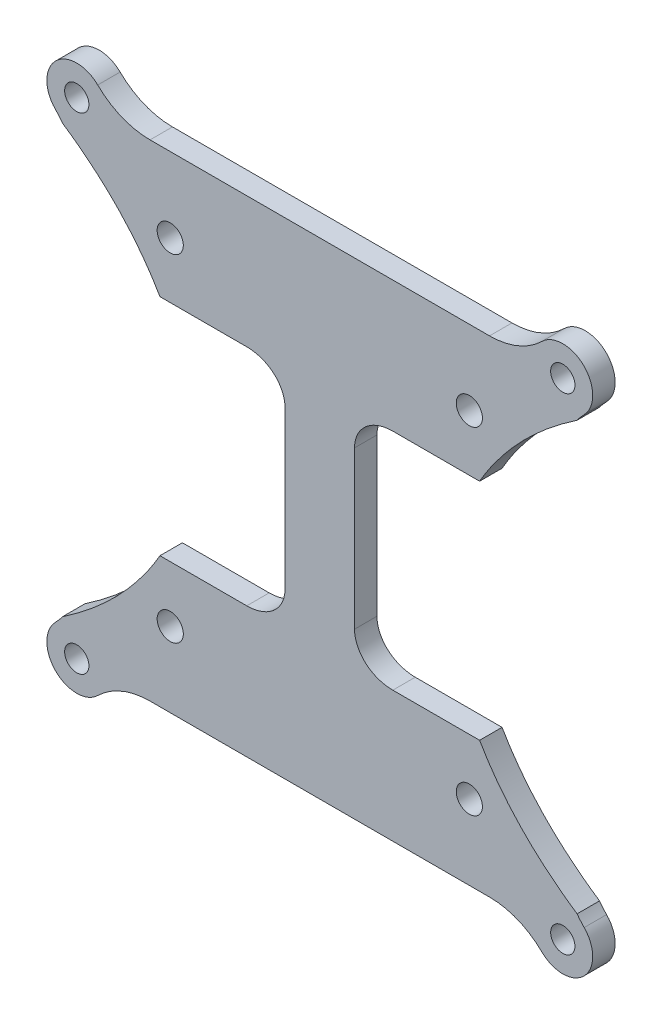
SolidWorks part; units mm, degrees
material "ABS"
ref_plane "Спереди" through (0, 0, 0) normal (0, 0, 1) x (1, 0, 0)
ref_plane "Сверху" through (0, 0, 0) normal (0, 1, 0) x (1, 0, 0)
ref_plane "Справа" through (0, 0, 0) normal (1, 0, 0) x (0, 0, -1)
sketch "Эскиз1" plane through (0, 0, 0) normal (0, 0, 1) x (1, 0, 0)
  line L1 (-32.5, -32.5) -> (32.5, -32.5)
  line L2 (-32.5, -32.5) -> (-32.5, 32.5)
  line L3 (-32.5, 32.5) -> (32.5, 32.5)
  line L4 (32.5, -32.5) -> (32.5, 32.5)
  line L5 (-32.5, -32.5) -> (32.5, 32.5) construction
  line L6 (-32.5, 32.5) -> (32.5, -32.5) construction
  circle A0 centre (-32.5, 32.5) radius 1.625
  arc A1 (-28.5, 32.5) -> (-32.5, 28.5) centre (-32.5, 32.5) ccw
  circle A2 centre (32.5, 32.5) radius 1.625
  arc A3 (32.5, 28.5) -> (28.5, 32.5) centre (32.5, 32.5) ccw
  circle A4 centre (32.5, -32.5) radius 1.625
  arc A5 (28.5, -32.5) -> (32.5, -28.5) centre (32.5, -32.5) ccw
  circle A6 centre (-32.5, -32.5) radius 1.625
  arc A7 (-32.5, -28.5) -> (-28.5, -32.5) centre (-32.5, -32.5) ccw
  point P0 (0, 0)
  point P20 (0, 0)
  dimension "D2" = 3.25
  dimension "D3" = 8
  dimension "D1" = 65
  dimension "D4" = 4
extrude "Бобышка-Вытянуть1" add sketch "Эскиз1" along normal blind 3 contours A6 L1 A4 L4 A2 L3 A0 L2 | L3 A1 L2 A0 | L4 A3 L3 A2 | L1 A5 L4 A4 | L2 A7 L1 A6
fillet "Скругление1" radius 10 8 edges at (-28.5, -32.5, 1.5) (-32.5, -28.5, 1.5) (-28.5, 32.5, 1.5) (-32.5, 28.5, 1.5) (28.5, 32.5, 1.5) (32.5, 28.5, 1.5) (32.5, -28.5, 1.5) (28.5, -32.5, 1.5)
sketch "Эскиз2" plane through (0, 0, 3) normal (0, 0, 1) x (1, 0, 0)
  line L0 (0, 32.5) -> (0, -32.5) construction
  line L1 (-22.702, 32.5) -> (22.702, 32.5) construction
  line L2 (-22.702, -32.5) -> (22.702, -32.5) construction
  line L3 (-32.5, 0) -> (32.5, 0) construction
  line L4 (-32.5, -22.702) -> (-32.5, 22.702) construction
  line L5 (32.5, -22.702) -> (32.5, 22.702) construction
  line L6 (-32.5, 22.5) -> (32.5, 22.5) construction
  circle A0 centre (-20, 22.5) radius 1.75
  circle A1 centre (20, 22.5) radius 1.75
  circle A2 centre (20, -22.5) radius 1.75
  circle A3 centre (-20, -22.5) radius 1.75
  dimension "D2" = 3.5
  dimension "D1" = 10
  dimension "D3" = 20
extrude "Вырез-Вытянуть1" cut sketch "Эскиз2" against normal blind 10
sketch "Эскиз3" plane through (0, 0, 3) normal (0, 0, 1) x (1, 0, 0)
  line L4 (-38.7591, -11.8255) -> (-40.1734, -10.8255)
  line L5 (-38.7591, -18.1012) -> (-38.7591, -11.8255)
  line L6 (-40.1734, -19.1012) -> (-38.7591, -18.1012)
  line L7 (-40.1734, -10.8255) -> (-40.1734, -19.1012)
  line L8 (-38.7591, -11.8255) -> (-40.1734, -10.8255)
  line L9 (-38.7591, -18.1012) -> (-38.7591, -11.8255)
  line L10 (-40.1734, -19.1012) -> (-38.7591, -18.1012)
  line L11 (-40.1734, -10.8255) -> (-40.1734, -19.1012)
  line L12 (38.7591, 11.8255) -> (40.1734, 10.8255)
  line L13 (38.7591, 18.1012) -> (38.7591, 11.8255)
  line L14 (-82.0001, -12.7701) -> (-81.8151, -12.8801)
  line L15 (-80.9227, -13.8292) -> (-80.0272, -15.612)
  line L16 (-79.1335, -15.9875) -> (-75.9847, -15.2389)
  line L17 (-75.694, 15.2742) -> (-79.1811, 15.9349)
  line L18 (-80.0623, 15.5421) -> (-80.9227, 13.8292)
  line L19 (-81.7613, 12.9159) -> (-81.993, 12.7739)
  line L20 (-82.0001, -12.7701) -> (-81.8151, -12.8801)
  line L21 (-80.9227, -13.8292) -> (-80.0272, -15.612)
  line L22 (-79.1335, -15.9875) -> (-75.9847, -15.2389)
  line L23 (-75.694, 15.2742) -> (-79.1811, 15.9349)
  line L24 (-80.0623, 15.5421) -> (-80.9227, 13.8292)
  line L25 (-81.7613, 12.9159) -> (-81.993, 12.7739)
  line L26 (40.1734, 19.1012) -> (38.7591, 18.1012)
  line L27 (40.1734, 10.8255) -> (40.1734, 19.1012)
  line L28 (38.7591, 11.8255) -> (40.1734, 10.8255)
  line L29 (38.7591, 18.1012) -> (38.7591, 11.8255)
  line L30 (40.1734, 19.1012) -> (38.7591, 18.1012)
  line L31 (40.1734, 10.8255) -> (40.1734, 19.1012)
  line L34 (-23.5994, 5.6485) -> (-23.5994, -5.6485)
  line L35 (-68.4576, -33.9999) -> (-68.4575, -34.4102)
  line L36 (-23.1698, -12) -> (-9.7678, -12)
  line L37 (-7.6464, -10.5) -> (-7.6464, 10.5)
  line L38 (-9.7678, 12) -> (-23.1698, 12)
  line L39 (-68.4576, 34.4102) -> (-68.4576, 33.9999)
  line L40 (-23.5994, 5.6485) -> (-23.5994, -5.6485)
  line L41 (-68.4576, -33.9999) -> (-68.4575, -34.4102)
  line L42 (-23.1698, -12) -> (-9.7678, -12)
  line L43 (-7.6464, -10.5) -> (-7.6464, 10.5)
  line L44 (-9.7678, 12) -> (-23.1698, 12)
  line L45 (-68.4576, 34.4102) -> (-68.4576, 33.9999)
  line L46 (82.0001, 12.7701) -> (81.8151, 12.8801)
  line L47 (80.9227, 13.8292) -> (80.0272, 15.612)
  line L48 (79.1335, 15.9875) -> (75.9847, 15.2389)
  line L49 (75.694, -15.2742) -> (79.1811, -15.9349)
  line L50 (80.0623, -15.5421) -> (80.9227, -13.8292)
  line L51 (81.7613, -12.9159) -> (81.993, -12.7739)
  line L52 (82.0001, 12.7701) -> (81.8151, 12.8801)
  line L53 (80.9227, 13.8292) -> (80.0272, 15.612)
  line L54 (79.1335, 15.9875) -> (75.9847, 15.2389)
  line L55 (75.694, -15.2742) -> (79.1811, -15.9349)
  line L56 (80.0623, -15.5421) -> (80.9227, -13.8292)
  line L57 (81.7613, -12.9159) -> (81.993, -12.7739)
  line L58 (23.5994, -5.6485) -> (23.5994, 5.6485)
  line L59 (68.4576, 33.9999) -> (68.4576, 34.4102)
  line L60 (23.1698, 12) -> (9.7678, 12)
  line L61 (7.6464, 10.5) -> (7.6464, -10.5)
  line L62 (9.7678, -12) -> (23.1698, -12)
  line L63 (68.4576, -34.4102) -> (68.4576, -33.9999)
  line L64 (23.5994, -5.6485) -> (23.5994, 5.6485)
  line L65 (68.4576, 33.9999) -> (68.4576, 34.4102)
  line L66 (23.1698, 12) -> (9.7678, 12)
  line L67 (7.6464, 10.5) -> (7.6464, -10.5)
  line L68 (9.7678, -12) -> (23.1698, -12)
  line L69 (68.4576, -34.4102) -> (68.4576, -33.9999)
  line L70 (71.4576, -34.4101) -> (71.4576, -31.1169)
  line L71 (9.7678, -15) -> (21.3752, -15)
  line L72 (4.6464, 10.5) -> (4.6464, -10.5)
  line L73 (21.3752, 15) -> (9.7678, 15)
  line L74 (71.4576, 31.1169) -> (71.4576, 34.4102)
  line L75 (26.5994, -5.2847) -> (26.5994, 5.2847)
  line L76 (71.4576, -34.4101) -> (71.4576, -31.1169)
  line L77 (9.7678, -15) -> (21.3752, -15)
  line L78 (4.6464, 10.5) -> (4.6464, -10.5)
  line L79 (21.3752, 15) -> (9.7678, 15)
  line L80 (71.4576, 31.1169) -> (71.4576, 34.4102)
  line L81 (26.5994, -5.2847) -> (26.5994, 5.2847)
  line L82 (-71.4576, 34.4109) -> (-71.4577, 31.1169)
  line L83 (-9.7678, 15) -> (-21.3752, 15)
  line L84 (-4.6464, -10.5) -> (-4.6464, 10.5)
  line L85 (-21.3752, -15) -> (-9.7678, -15)
  line L86 (-71.4587, -31.117) -> (-71.4575, -34.4505)
  line L87 (-26.5994, 5.2847) -> (-26.5994, -5.2847)
  line L88 (-71.4576, 34.4109) -> (-71.4577, 31.1169)
  line L89 (-9.7678, 15) -> (-21.3752, 15)
  line L90 (-4.6464, -10.5) -> (-4.6464, 10.5)
  line L91 (-21.3752, -15) -> (-9.7678, -15)
  line L92 (-71.4587, -31.117) -> (-71.4575, -34.4505)
  line L93 (-26.5994, 5.2847) -> (-26.5994, -5.2847)
  spline S1 degree 3 poles (-10.4749, -7.5) (-10.4749, -3.5) (-16.1317, -3.5) (-16.1317, -7.5) (-16.1317, -11.5) (-10.4749, -11.5) (-10.4749, -7.5) (-10.4749, -3.5) (-16.1317, -3.5) knots -0.5 0 0 0 0.5 0.5 0.5 1 1 1 1.5 1.5 1.5 weights 1 0.333333 0.333333 1 0.333333 0.333333 1 0.333333 0.333333 only from (-10.4749, -7.5) to (-10.4749, -7.5)
  spline S2 degree 3 poles (-10.4749, -7.5) (-10.4749, -3.5) (-16.1317, -3.5) (-16.1317, -7.5) (-16.1317, -11.5) (-10.4749, -11.5) (-10.4749, -7.5) (-10.4749, -3.5) (-16.1317, -3.5) knots -0.5 0 0 0 0.5 0.5 0.5 1 1 1 1.5 1.5 1.5 weights 1 0.333333 0.333333 1 0.333333 0.333333 1 0.333333 0.333333 only from (-10.4749, -7.5) to (-10.4749, -7.5)
  spline S3 degree 3 poles (-10.4749, 7.5) (-10.4749, 11.5) (-16.1317, 11.5) (-16.1317, 7.5) (-16.1317, 3.5) (-10.4749, 3.5) (-10.4749, 7.5) (-10.4749, 11.5) (-16.1317, 11.5) knots -0.5 0 0 0 0.5 0.5 0.5 1 1 1 1.5 1.5 1.5 weights 1 0.333333 0.333333 1 0.333333 0.333333 1 0.333333 0.333333 only from (-10.4749, 7.5) to (-10.4749, 7.5)
  spline S4 degree 3 poles (-10.4749, 7.5) (-10.4749, 11.5) (-16.1317, 11.5) (-16.1317, 7.5) (-16.1317, 3.5) (-10.4749, 3.5) (-10.4749, 7.5) (-10.4749, 11.5) (-16.1317, 11.5) knots -0.5 0 0 0 0.5 0.5 0.5 1 1 1 1.5 1.5 1.5 weights 1 0.333333 0.333333 1 0.333333 0.333333 1 0.333333 0.333333 only from (-10.4749, 7.5) to (-10.4749, 7.5)
  spline S5 degree 3 poles (10.4749, 7.5) (10.4749, 3.5) (16.1317, 3.5) (16.1317, 7.5) (16.1317, 11.5) (10.4749, 11.5) (10.4749, 7.5) (10.4749, 3.5) (16.1317, 3.5) knots -0.5 0 0 0 0.5 0.5 0.5 1 1 1 1.5 1.5 1.5 weights 1 0.333333 0.333333 1 0.333333 0.333333 1 0.333333 0.333333 only from (10.4749, 7.5) to (10.4749, 7.5)
  spline S6 degree 3 poles (10.4749, 7.5) (10.4749, 3.5) (16.1317, 3.5) (16.1317, 7.5) (16.1317, 11.5) (10.4749, 11.5) (10.4749, 7.5) (10.4749, 3.5) (16.1317, 3.5) knots -0.5 0 0 0 0.5 0.5 0.5 1 1 1 1.5 1.5 1.5 weights 1 0.333333 0.333333 1 0.333333 0.333333 1 0.333333 0.333333 only from (10.4749, 7.5) to (10.4749, 7.5)
  spline S7 degree 3 poles (10.4749, -7.5) (10.4749, -11.5) (16.1317, -11.5) (16.1317, -7.5) (16.1317, -3.5) (10.4749, -3.5) (10.4749, -7.5) (10.4749, -11.5) (16.1317, -11.5) knots -0.5 0 0 0 0.5 0.5 0.5 1 1 1 1.5 1.5 1.5 weights 1 0.333333 0.333333 1 0.333333 0.333333 1 0.333333 0.333333 only from (10.4749, -7.5) to (10.4749, -7.5)
  spline S8 degree 3 poles (10.4749, -7.5) (10.4749, -11.5) (16.1317, -11.5) (16.1317, -7.5) (16.1317, -3.5) (10.4749, -3.5) (10.4749, -7.5) (10.4749, -11.5) (16.1317, -11.5) knots -0.5 0 0 0 0.5 0.5 0.5 1 1 1 1.5 1.5 1.5 weights 1 0.333333 0.333333 1 0.333333 0.333333 1 0.333333 0.333333 only from (10.4749, -7.5) to (10.4749, -7.5)
  spline S16 degree 3 poles (-23.5994, -5.6485) (-27.4964, -22.0038) (-45.0004, -33.0667) (-68.4576, -33.9999) knots 0 0 0 0 1 1 1 1 weights 1 0.854251 0.854251 1
  spline S17 degree 3 poles (-2063.8023, -169.9528) (-48.9095, -26.3357) (-68.9345, -31.2035) (-68.4405, -34.6081) (-68.4142, -34.7204) (-68.3493, -34.9029) (-68.2007, -35.1493) (-67.9533, -35.395) (-67.6517, -35.5947) (-67.3374, -35.7342) (-66.9897, -35.8321) (-66.6982, -35.8734) (-60.2525, -36.1728) (-54.0031, -9.3917) (-42.6478, -2035.6643) knots -3.357469 -3.357469 -3.357469 -3.357469 0.033193 0.06659 0.100333 0.149309 0.261141 0.386702 0.497425 0.623884 0.731384 0.860481 0.9194 7.225792 7.225792 7.225792 7.225792 only from (-68.4575, -34.4102) to (-66.2132, -35.8754)
  spline S18 degree 3 poles (1480.429, 1254.4685) (-52.2846, 6.6497) (-74.2357, 20.3281) (-85.9765, 10.0439) (-86.2382, 9.8032) (-86.4915, 9.5581) (-86.9723, 9.0696) (-87.637, 8.3075) (-88.4098, 7.2278) (-89.1848, 5.8925) (-89.8783, 4.2706) (-90.3804, 2.3398) (-90.5866, 0.3596) (-90.489, -1.6318) (-90.0914, -3.5903) (-89.4067, -5.4592) (-88.4482, -7.2191) (-87.5257, -8.4479) (-86.7993, -9.2478) (-86.3671, -9.6837) (-66.7238, -27.9076) (32.2772, -15.1108) (-1144.9131, 1684.0441) knots -1.888033 -1.888033 -1.888033 -1.888033 0.014985 0.029837 0.044559 0.059151 0.073617 0.129706 0.184548 0.238313 0.321232 0.402799 0.485249 0.567587 0.649509 0.732567 0.813893 0.897623 0.92268 0.948089 0.973859 4.292326 4.292326 4.292326 4.292326 only from (-85.4284, 10.5101) to (-85.4283, -10.5101)
  spline S19 degree 3 poles (-85.4283, -10.5101) (-84.3984, -11.3461) (-83.2515, -12.1021) (-82.0001, -12.7701) knots 0 0 0 0 1 1 1 1 weights 1 0.996415 0.996415 1
  spline S20 degree 3 poles (-1326.947, 1552.1577) (-12.7734, -66.3768) (-85.4859, -10.1805) (-81.5604, -13.0632) (-81.4203, -13.1863) (-81.3058, -13.2991) (-81.2068, -13.4081) (-81.1175, -13.5185) (-81.0411, -13.6256) (-79.2369, -16.5345) (-101.1697, 7.9874) (1046.3151, -1665.799) knots -6.972307 -6.972307 -6.972307 -6.972307 0.075826 0.250212 0.388522 0.500519 0.616073 0.723814 0.823719 0.915779 7.414882 7.414882 7.414882 7.414882 only from (-81.8151, -12.8801) to (-80.9227, -13.8292)
  spline S21 degree 3 poles (-80.0272, -15.612) (-79.8643, -15.9364) (-79.5225, -16.08) (-79.1335, -15.9875) knots 0 0 0 0 1 1 1 1 weights 1 0.8715 0.8715 1
  spline S22 degree 3 poles (-75.9847, -15.2389) (-75.7539, -15.1841) (-75.5104, -15.1829) (-75.2786, -15.2354) knots 0 0 0 0 1 1 1 1 weights 1 0.966708 0.966708 1
  spline S23 degree 3 poles (-75.2786, -15.2354) (-59.3562, -18.8468) (-45.8227, -11.9024) (-45.7404, -0.0787) (-45.6581, 11.7449) (-59.0944, 18.7831) (-75.0662, 15.2828) knots 0 0 0 0 0.5 0.5 0.5 1 1 1 1 weights 1 0.727531 0.727531 1 0.727531 0.727531 1
  spline S24 degree 3 poles (-75.0662, 15.2828) (-75.2715, 15.2378) (-75.4864, 15.2349) (-75.694, 15.2742) knots 0 0 0 0 1 1 1 1 weights 1 0.97382 0.97382 1
  spline S25 degree 3 poles (-79.1811, 15.9349) (-79.5679, 16.0082) (-79.9033, 15.8587) (-80.0623, 15.5421) knots 0 0 0 0 1 1 1 1 weights 1 0.875797 0.875797 1
  spline S26 degree 3 poles (1324.0559, 1437.0711) (-117.5999, -9.2904) (-77.8453, 18.1901) (-81.137, 13.4904) (-81.2675, 13.3383) (-81.3962, 13.2091) (-81.5125, 13.1046) (-96.3555, 1.0895) (-202.357, 157.0318) (1267.0645, -1463.7366) knots -11.592483 -11.592483 -11.592483 -11.592483 0.146316 0.313382 0.501172 0.625961 0.750142 0.875463 46.138666 46.138666 46.138666 46.138666 only from (-80.9227, 13.8292) to (-81.7613, 12.9159)
  spline S27 degree 3 poles (-81.993, 12.7739) (-83.2472, 12.105) (-84.3964, 11.3476) (-85.4284, 10.5101) knots 0 0 0 0 1 1 1 1 weights 1 0.996402 0.996402 1
  spline S28 degree 3 poles (-85.4284, 10.5101) (-85.522, 10.434) (-85.7058, 10.2811) (-85.9765, 10.0439) (-86.2382, 9.8032) (-86.4915, 9.5581) (-86.9723, 9.0696) (-87.637, 8.3075) (-88.4098, 7.2278) (-89.1848, 5.8925) (-89.8783, 4.2706) (-90.3804, 2.3398) (-90.5866, 0.3596) (-90.489, -1.6318) (-90.0914, -3.5903) (-89.4067, -5.4592) (-88.4482, -7.2191) (-87.5257, -8.4479) (-86.7993, -9.2478) (-86.3671, -9.6837) (-85.9163, -10.1019) (-85.5946, -10.3752) (-85.4283, -10.5101) knots 0 0 0 0 0.014985 0.029837 0.044559 0.059151 0.073617 0.129706 0.184548 0.238313 0.321232 0.402799 0.485249 0.567587 0.649509 0.732567 0.813893 0.897623 0.92268 0.948089 0.973859 1 1 1 1
  spline S29 degree 3 poles (-85.4283, -10.5101) (-84.3984, -11.3461) (-83.2515, -12.1021) (-82.0001, -12.7701) knots 0 0 0 0 1 1 1 1 weights 1 0.996415 0.996415 1
  spline S30 degree 3 poles (-81.8151, -12.8801) (-81.8092, -12.8839) (-81.7676, -12.9111) (-81.5604, -13.0632) (-81.4203, -13.1863) (-81.3058, -13.2991) (-81.2068, -13.4081) (-81.1175, -13.5185) (-81.0411, -13.6256) (-80.9666, -13.7456) (-80.936, -13.8027) (-80.9227, -13.8292) knots 0 0 0 0 0.075826 0.250212 0.388522 0.500519 0.616073 0.723814 0.823719 0.915779 1 1 1 1
  spline S31 degree 3 poles (-80.0272, -15.612) (-79.8643, -15.9364) (-79.5225, -16.08) (-79.1335, -15.9875) knots 0 0 0 0 1 1 1 1 weights 1 0.8715 0.8715 1
  spline S32 degree 3 poles (-75.9847, -15.2389) (-75.7539, -15.1841) (-75.5104, -15.1829) (-75.2786, -15.2354) knots 0 0 0 0 1 1 1 1 weights 1 0.966708 0.966708 1
  spline S33 degree 3 poles (-75.2786, -15.2354) (-59.3562, -18.8468) (-45.8227, -11.9024) (-45.7404, -0.0787) (-45.6581, 11.7449) (-59.0944, 18.7831) (-75.0662, 15.2828) knots 0 0 0 0 0.5 0.5 0.5 1 1 1 1 weights 1 0.727531 0.727531 1 0.727531 0.727531 1
  spline S34 degree 3 poles (-75.0662, 15.2828) (-75.2715, 15.2378) (-75.4864, 15.2349) (-75.694, 15.2742) knots 0 0 0 0 1 1 1 1 weights 1 0.97382 0.97382 1
  spline S35 degree 3 poles (-79.1811, 15.9349) (-79.5679, 16.0082) (-79.9033, 15.8587) (-80.0623, 15.5421) knots 0 0 0 0 1 1 1 1 weights 1 0.875797 0.875797 1
  spline S36 degree 3 poles (-80.9227, 13.8292) (-80.9451, 13.7847) (-81.0006, 13.6851) (-81.137, 13.4904) (-81.2675, 13.3383) (-81.3962, 13.2091) (-81.5125, 13.1046) (-81.6344, 13.0059) (-81.7187, 12.945) (-81.7613, 12.9159) knots 0 0 0 0 0.146316 0.313382 0.501172 0.625961 0.750142 0.875463 1 1 1 1
  spline S37 degree 3 poles (-81.993, 12.7739) (-83.2472, 12.105) (-84.3964, 11.3476) (-85.4284, 10.5101) knots 0 0 0 0 1 1 1 1 weights 1 0.996402 0.996402 1
  spline S38 degree 3 poles (-66.2132, -35.8754) (-45.9554, -34.4336) (-29.9459, -25.5534) (-23.1698, -12) knots 0 0 0 0 1 1 1 1 weights 1 0.896207 0.896207 1
  spline S39 degree 3 poles (-9.7678, -12) (-8.5251, -12) (-7.6464, -11.3787) (-7.6464, -10.5) knots 0 0 0 0 1 1 1 1 weights 1 0.804738 0.804738 1
  spline S40 degree 3 poles (-7.6464, 10.5) (-7.6464, 11.3787) (-8.5251, 12) (-9.7678, 12) knots 0 0 0 0 1 1 1 1 weights 1 0.804738 0.804738 1
  spline S41 degree 3 poles (-23.1698, 12) (-29.9459, 25.5534) (-45.9553, 34.4336) (-66.2131, 35.8754) knots 0 0 0 0 1 1 1 1 weights 1 0.896207 0.896207 1
  spline S42 degree 3 poles (-1949.7047, 706.2139) (-44.4675, -46.1989) (-53.9994, 35.5971) (-66.4941, 35.8853) (-66.7631, 35.8695) (-67.1233, 35.8008) (-67.4532, 35.6896) (-67.7786, 35.5205) (-68.0573, 35.3049) (-68.248, 35.0751) (-68.356, 34.8784) (-68.4144, 34.7238) (-69.8472, 28.2623) (-11.8572, 42.007) (-800.7877, -1826.2233) knots -12.395033 -12.395033 -12.395033 -12.395033 0.030465 0.060951 0.191843 0.300888 0.429435 0.541045 0.668884 0.781672 0.839039 0.894208 0.947683 7.236923 7.236923 7.236923 7.236923 only from (-66.2131, 35.8754) to (-68.4576, 34.4102)
  spline S43 degree 3 poles (-68.4576, 33.9999) (-45.0004, 33.0667) (-27.4964, 22.0038) (-23.5994, 5.6485) knots 0 0 0 0 1 1 1 1 weights 1 0.854251 0.854251 1
  spline S44 degree 3 poles (-23.5994, -5.6485) (-27.4964, -22.0038) (-45.0004, -33.0667) (-68.4576, -33.9999) knots 0 0 0 0 1 1 1 1 weights 1 0.854251 0.854251 1
  spline S45 degree 3 poles (-68.4575, -34.4102) (-68.4566, -34.4432) (-68.4549, -34.5093) (-68.4405, -34.6081) (-68.4142, -34.7204) (-68.3493, -34.9029) (-68.2007, -35.1493) (-67.9533, -35.395) (-67.6517, -35.5947) (-67.3374, -35.7342) (-66.9897, -35.8321) (-66.6982, -35.8734) (-66.4316, -35.8858) (-66.2932, -35.8792) (-66.2132, -35.8754) knots 0 0 0 0 0.033193 0.06659 0.100333 0.149309 0.261141 0.386702 0.497425 0.623884 0.731384 0.860481 0.9194 1 1 1 1
  spline S46 degree 3 poles (-66.2132, -35.8754) (-45.9554, -34.4336) (-29.9459, -25.5534) (-23.1698, -12) knots 0 0 0 0 1 1 1 1 weights 1 0.896207 0.896207 1
  spline S47 degree 3 poles (-9.7678, -12) (-8.5251, -12) (-7.6464, -11.3787) (-7.6464, -10.5) knots 0 0 0 0 1 1 1 1 weights 1 0.804738 0.804738 1
  spline S48 degree 3 poles (-7.6464, 10.5) (-7.6464, 11.3787) (-8.5251, 12) (-9.7678, 12) knots 0 0 0 0 1 1 1 1 weights 1 0.804738 0.804738 1
  spline S49 degree 3 poles (-23.1698, 12) (-29.9459, 25.5534) (-45.9553, 34.4336) (-66.2131, 35.8754) knots 0 0 0 0 1 1 1 1 weights 1 0.896207 0.896207 1
  spline S50 degree 3 poles (-66.2131, 35.8754) (-66.2433, 35.8775) (-66.3037, 35.8809) (-66.4941, 35.8853) (-66.7631, 35.8695) (-67.1233, 35.8008) (-67.4532, 35.6896) (-67.7786, 35.5205) (-68.0573, 35.3049) (-68.248, 35.0751) (-68.356, 34.8784) (-68.4144, 34.7238) (-68.4504, 34.5612) (-68.4576, 34.46) (-68.4576, 34.4102) knots 0 0 0 0 0.030465 0.060951 0.191843 0.300888 0.429435 0.541045 0.668884 0.781672 0.839039 0.894208 0.947683 1 1 1 1
  spline S51 degree 3 poles (-68.4576, 33.9999) (-45.0004, 33.0667) (-27.4964, 22.0038) (-23.5994, 5.6485) knots 0 0 0 0 1 1 1 1 weights 1 0.854251 0.854251 1
  spline S52 degree 3 poles (23.5994, 5.6485) (27.4964, 22.0038) (45.0004, 33.0667) (68.4576, 33.9999) knots 0 0 0 0 1 1 1 1 weights 1 0.854251 0.854251 1
  spline S53 degree 3 poles (1069.6876, -1696.8561) (67.4785, 32.9048) (68.6356, 33.7336) (68.3988, 34.8283) (68.1289, 35.262) (67.6406, 35.6348) (66.9563, 35.8627) (65.1677, 36.0185) (56.0596, 33.7798) (2063.6845, -62.5821) knots -0.819423 -0.819423 -0.819423 -0.819423 0.00005 0.148857 0.270885 0.510832 0.751134 0.991618 2.683844 2.683844 2.683844 2.683844 only from (68.4576, 34.4102) to (66.2132, 35.8754)
  spline S54 degree 3 poles (-1480.429, -1254.4685) (52.2846, -6.6497) (74.2357, -20.3281) (85.9765, -10.0439) (86.2382, -9.8032) (86.4915, -9.5581) (86.9723, -9.0696) (87.637, -8.3075) (88.4098, -7.2278) (89.1848, -5.8925) (89.8783, -4.2706) (90.3804, -2.3398) (90.5866, -0.3596) (90.489, 1.6318) (90.0914, 3.5903) (89.4067, 5.4592) (88.4482, 7.2191) (87.5257, 8.4479) (86.7993, 9.2478) (86.3671, 9.6837) (66.7238, 27.9076) (-32.2772, 15.1108) (1144.9131, -1684.0441) knots -1.888033 -1.888033 -1.888033 -1.888033 0.014985 0.029837 0.044559 0.059151 0.073617 0.129706 0.184548 0.238313 0.321232 0.402799 0.485249 0.567587 0.649509 0.732567 0.813893 0.897623 0.92268 0.948089 0.973859 4.292326 4.292326 4.292326 4.292326 only from (85.4284, -10.5101) to (85.4283, 10.5101)
  spline S55 degree 3 poles (85.4283, 10.5101) (84.3984, 11.3461) (83.2515, 12.1021) (82.0001, 12.7701) knots 0 0 0 0 1 1 1 1 weights 1 0.996415 0.996415 1
  spline S56 degree 3 poles (1326.947, -1552.1578) (12.7734, 66.3768) (85.4859, 10.1805) (81.5604, 13.0632) (81.4203, 13.1863) (81.3058, 13.2991) (81.2068, 13.4081) (81.1175, 13.5185) (81.0411, 13.6256) (79.2369, 16.5345) (101.1697, -7.9873) (-1046.3151, 1665.7949) knots -6.972307 -6.972307 -6.972307 -6.972307 0.075826 0.250212 0.388522 0.500519 0.616073 0.723814 0.823719 0.915779 7.414882 7.414882 7.414882 7.414882 only from (81.8151, 12.8801) to (80.9227, 13.8292)
  spline S57 degree 3 poles (80.0272, 15.612) (79.8643, 15.9364) (79.5225, 16.08) (79.1335, 15.9875) knots 0 0 0 0 1 1 1 1 weights 1 0.8715 0.8715 1
  spline S58 degree 3 poles (75.9847, 15.2389) (75.7539, 15.1841) (75.5104, 15.1829) (75.2786, 15.2354) knots 0 0 0 0 1 1 1 1 weights 1 0.966708 0.966708 1
  spline S59 degree 3 poles (75.2786, 15.2354) (59.3562, 18.8468) (45.8227, 11.9024) (45.7404, 0.0787) (45.6581, -11.7449) (59.0944, -18.7831) (75.0662, -15.2828) knots 0 0 0 0 0.5 0.5 0.5 1 1 1 1 weights 1 0.727531 0.727531 1 0.727531 0.727531 1
  spline S60 degree 3 poles (75.0662, -15.2828) (75.2715, -15.2378) (75.4864, -15.2349) (75.694, -15.2742) knots 0 0 0 0 1 1 1 1 weights 1 0.97382 0.97382 1
  spline S61 degree 3 poles (79.1811, -15.9349) (79.5679, -16.0082) (79.9033, -15.8587) (80.0623, -15.5421) knots 0 0 0 0 1 1 1 1 weights 1 0.875797 0.875797 1
  spline S62 degree 3 poles (-1324.0559, -1437.0711) (117.5999, 9.2904) (77.8453, -18.1901) (81.137, -13.4904) (81.2675, -13.3383) (81.3962, -13.2091) (81.5125, -13.1046) (96.3555, -1.0895) (202.357, -157.0318) (-1267.0645, 1463.7366) knots -11.592483 -11.592483 -11.592483 -11.592483 0.146316 0.313382 0.501172 0.625961 0.750142 0.875463 46.138666 46.138666 46.138666 46.138666 only from (80.9227, -13.8292) to (81.7613, -12.9159)
  spline S63 degree 3 poles (81.993, -12.7739) (83.2472, -12.105) (84.3964, -11.3476) (85.4284, -10.5101) knots 0 0 0 0 1 1 1 1 weights 1 0.996402 0.996402 1
  spline S64 degree 3 poles (85.4284, -10.5101) (85.522, -10.434) (85.7058, -10.2811) (85.9765, -10.0439) (86.2382, -9.8032) (86.4915, -9.5581) (86.9723, -9.0696) (87.637, -8.3075) (88.4098, -7.2278) (89.1848, -5.8925) (89.8783, -4.2706) (90.3804, -2.3398) (90.5866, -0.3596) (90.489, 1.6318) (90.0914, 3.5903) (89.4067, 5.4592) (88.4482, 7.2191) (87.5257, 8.4479) (86.7993, 9.2478) (86.3671, 9.6837) (85.9163, 10.1019) (85.5946, 10.3752) (85.4283, 10.5101) knots 0 0 0 0 0.014985 0.029837 0.044559 0.059151 0.073617 0.129706 0.184548 0.238313 0.321232 0.402799 0.485249 0.567587 0.649509 0.732567 0.813893 0.897623 0.92268 0.948089 0.973859 1 1 1 1
  spline S65 degree 3 poles (85.4283, 10.5101) (84.3984, 11.3461) (83.2515, 12.1021) (82.0001, 12.7701) knots 0 0 0 0 1 1 1 1 weights 1 0.996415 0.996415 1
  spline S66 degree 3 poles (81.8151, 12.8801) (81.8092, 12.8839) (81.7676, 12.9111) (81.5604, 13.0632) (81.4203, 13.1863) (81.3058, 13.2991) (81.2068, 13.4081) (81.1175, 13.5185) (81.0411, 13.6256) (80.9666, 13.7456) (80.936, 13.8027) (80.9227, 13.8292) knots 0 0 0 0 0.075826 0.250212 0.388522 0.500519 0.616073 0.723814 0.823719 0.915779 1 1 1 1
  spline S67 degree 3 poles (80.0272, 15.612) (79.8643, 15.9364) (79.5225, 16.08) (79.1335, 15.9875) knots 0 0 0 0 1 1 1 1 weights 1 0.8715 0.8715 1
  spline S68 degree 3 poles (75.9847, 15.2389) (75.7539, 15.1841) (75.5104, 15.1829) (75.2786, 15.2354) knots 0 0 0 0 1 1 1 1 weights 1 0.966708 0.966708 1
  spline S69 degree 3 poles (75.2786, 15.2354) (59.3562, 18.8468) (45.8227, 11.9024) (45.7404, 0.0787) (45.6581, -11.7449) (59.0944, -18.7831) (75.0662, -15.2828) knots 0 0 0 0 0.5 0.5 0.5 1 1 1 1 weights 1 0.727531 0.727531 1 0.727531 0.727531 1
  spline S70 degree 3 poles (75.0662, -15.2828) (75.2715, -15.2378) (75.4864, -15.2349) (75.694, -15.2742) knots 0 0 0 0 1 1 1 1 weights 1 0.97382 0.97382 1
  spline S71 degree 3 poles (79.1811, -15.9349) (79.5679, -16.0082) (79.9033, -15.8587) (80.0623, -15.5421) knots 0 0 0 0 1 1 1 1 weights 1 0.875797 0.875797 1
  spline S72 degree 3 poles (80.9227, -13.8292) (80.9451, -13.7847) (81.0006, -13.6851) (81.137, -13.4904) (81.2675, -13.3383) (81.3962, -13.2091) (81.5125, -13.1046) (81.6344, -13.0059) (81.7187, -12.945) (81.7613, -12.9159) knots 0 0 0 0 0.146316 0.313382 0.501172 0.625961 0.750142 0.875463 1 1 1 1
  spline S73 degree 3 poles (81.993, -12.7739) (83.2472, -12.105) (84.3964, -11.3476) (85.4284, -10.5101) knots 0 0 0 0 1 1 1 1 weights 1 0.996402 0.996402 1
  spline S74 degree 3 poles (66.2132, 35.8754) (45.9554, 34.4336) (29.9459, 25.5534) (23.1698, 12) knots 0 0 0 0 1 1 1 1 weights 1 0.896207 0.896207 1
  spline S75 degree 3 poles (9.7678, 12) (8.5251, 12) (7.6464, 11.3787) (7.6464, 10.5) knots 0 0 0 0 1 1 1 1 weights 1 0.804738 0.804738 1
  spline S76 degree 3 poles (7.6464, -10.5) (7.6464, -11.3787) (8.5251, -12) (9.7678, -12) knots 0 0 0 0 1 1 1 1 weights 1 0.804738 0.804738 1
  spline S77 degree 3 poles (23.1698, -12) (29.9459, -25.5534) (45.9554, -34.4336) (66.2132, -35.8754) knots 0 0 0 0 1 1 1 1 weights 1 0.896207 0.896207 1
  spline S78 degree 3 poles (2066.1658, -26.9396) (40.6267, -32.5264) (65.1107, -35.9977) (66.6934, -35.8767) (67.1624, -35.7998) (67.6079, -35.6348) (67.9987, -35.3577) (68.2464, -35.0892) (68.4137, -34.7756) (68.8654, -32.1897) (60.8218, -32.9626) (572.6506, 1900.9201) knots -2.091743 -2.091743 -2.091743 -2.091743 0.035741 0.172478 0.275349 0.514926 0.642895 0.755601 0.88057 0.996324 3.299965 3.299965 3.299965 3.299965 only from (66.2132, -35.8754) to (68.4576, -34.4102)
  spline S79 degree 3 poles (68.4576, -33.9999) (45.0004, -33.0667) (27.4964, -22.0038) (23.5994, -5.6485) knots 0 0 0 0 1 1 1 1 weights 1 0.854251 0.854251 1
  spline S80 degree 3 poles (23.5994, 5.6485) (27.4964, 22.0038) (45.0004, 33.0667) (68.4576, 33.9999) knots 0 0 0 0 1 1 1 1 weights 1 0.854251 0.854251 1
  spline S81 degree 3 poles (68.4576, 34.4102) (68.4576, 34.4102) (68.4576, 34.5563) (68.3988, 34.8283) (68.1289, 35.262) (67.6406, 35.6348) (66.9563, 35.8627) (66.5537, 35.8978) (66.2242, 35.8762) (66.2132, 35.8754) knots 0 0 0 0 0.00005 0.148857 0.270885 0.510832 0.751134 0.991618 1 1 1 1
  spline S82 degree 3 poles (66.2132, 35.8754) (45.9554, 34.4336) (29.9459, 25.5534) (23.1698, 12) knots 0 0 0 0 1 1 1 1 weights 1 0.896207 0.896207 1
  spline S83 degree 3 poles (9.7678, 12) (8.5251, 12) (7.6464, 11.3787) (7.6464, 10.5) knots 0 0 0 0 1 1 1 1 weights 1 0.804738 0.804738 1
  spline S84 degree 3 poles (7.6464, -10.5) (7.6464, -11.3787) (8.5251, -12) (9.7678, -12) knots 0 0 0 0 1 1 1 1 weights 1 0.804738 0.804738 1
  spline S85 degree 3 poles (23.1698, -12) (29.9459, -25.5534) (45.9554, -34.4336) (66.2132, -35.8754) knots 0 0 0 0 1 1 1 1 weights 1 0.896207 0.896207 1
  spline S86 degree 3 poles (66.2132, -35.8754) (66.2607, -35.8788) (66.5093, -35.8908) (66.6934, -35.8767) (67.1624, -35.7998) (67.6079, -35.6348) (67.9987, -35.3577) (68.2464, -35.0892) (68.4137, -34.7756) (68.4571, -34.5272) (68.4576, -34.4137) (68.4576, -34.4102) knots 0 0 0 0 0.035741 0.172478 0.275349 0.514926 0.642895 0.755601 0.88057 0.996324 1 1 1 1
  spline S87 degree 3 poles (68.4576, -33.9999) (45.0004, -33.0667) (27.4964, -22.0038) (23.5994, -5.6485) knots 0 0 0 0 1 1 1 1 weights 1 0.854251 0.854251 1
  spline S88 degree 3 poles (2064.6421, 33.5609) (33.825, -35.2501) (62.7246, -38.7783) (66.4859, -38.8884) (67.0561, -38.8654) (67.3818, -38.8096) (67.919, -38.6911) (68.4389, -38.5289) (69.1033, -38.2395) (69.8926, -37.7129) (70.6516, -36.9474) (71.1817, -35.9977) (74.3456, -24.0775) (27.7881, 16.615) (-639.251, -1903.2493) knots -1.730076 -1.730076 -1.730076 -1.730076 0.031251 0.0625 0.124999 0.249997 0.312495 0.374994 0.499992 0.624989 0.749987 0.874985 0.937483 4.162579 4.162579 4.162579 4.162579 only from (66.0002, -38.8678) to (71.4576, -34.4101)
  spline S89 degree 3 poles (-887.9346, 1765.742) (50.2868, 50.9699) (-0.0618, 13.4883) (25.1101, -20.4617) (28.5486, -24.1421) (33.5353, -28.1546) (39.2593, -31.6373) (45.5625, -34.5007) (52.2583, -36.6859) (57.9942, -37.9239) (119.7919, -46.6545) (159.4132, 19.54) (2062.0825, -152.3239) knots -2.347067 -2.347067 -2.347067 -2.347067 0.101413 0.161318 0.28113 0.400942 0.520753 0.640565 0.760377 0.880188 0.940094 3.982121 3.982121 3.982121 3.982121 only from (21.3752, -15) to (66.0002, -38.8678)
  spline S90 degree 3 poles (954.012, -1768.4463) (85.9707, 85.9206) (-7.037, -0.1525) (6.4997, -14.1416) (7.9063, -14.752) (22.2202, -17.5833) (8.9565, 28.48) (1983.34, -337.1081) knots -6.146973 -6.146973 -6.146973 -6.146973 0.25 0.5 0.75 0.875 7.024536 7.024536 7.024536 7.024536 only from (4.6464, -10.5) to (9.7678, -15)
  spline S91 degree 3 poles (1983.3173, 337.1039) (8.9566, -28.4796) (22.2201, 17.5833) (7.9063, 14.752) (6.4997, 14.1416) (-7.037, 0.1525) (85.9707, -85.9206) (954.012, 1768.4463) knots -6.024513 -6.024513 -6.024513 -6.024513 0.125 0.25 0.5 0.75 7.146973 7.146973 7.146973 7.146973 only from (9.7678, 15) to (4.6464, 10.5)
  spline S92 degree 3 poles (2062.1449, 152.3302) (159.414, -19.5413) (119.7925, 46.6546) (57.9942, 37.9239) (52.2583, 36.6859) (45.5625, 34.5007) (39.2593, 31.6372) (33.5353, 28.1546) (28.5486, 24.1421) (25.1101, 20.4617) (-0.0617, -13.4882) (50.2867, -50.9697) (-887.9288, -1765.7324) knots -2.982155 -2.982155 -2.982155 -2.982155 0.059906 0.119812 0.239623 0.359435 0.479247 0.599058 0.71887 0.838682 0.898587 3.347063 3.347063 3.347063 3.347063 only from (66.0002, 38.8678) to (21.3752, 15)
  spline S93 degree 3 poles (-594.4904, 1919.8538) (35.0677, -16.9124) (74.1152, 25.0129) (71.1816, 35.9966) (70.6499, 36.9501) (69.8939, 37.7115) (69.099, 38.2426) (68.3136, 38.58) (56.6948, 41.9984) (-14.6227, 6.5785) (2020.01, -385.9158) knots -2.926774 -2.926774 -2.926774 -2.926774 0.0625 0.125 0.25 0.375 0.5 0.625 0.75 6.991869 6.991869 6.991869 6.991869 only from (71.4576, 34.4102) to (66.0002, 38.8678)
  spline S94 degree 3 poles (-480.9363, -1928.6152) (78.484, -33.4384) (14.5483, -21.3347) (28.3902, 10.155) (29.8041, 12.6019) (32.1499, 15.8283) (35.951, 19.6978) (41.7938, 23.7968) (48.6472, 27.1004) (56.1314, 29.4491) (61.913, 30.4585) (65.7107, 30.8341) (67.2917, 30.9441) (68.5214, 31.0014) (106.8878, 32.4681) (121.8966, 36.4312) (2061.257, -169.3057) knots -2.287871 -2.287871 -2.287871 -2.287871 0.073907 0.138841 0.203776 0.26871 0.398578 0.528447 0.658315 0.788183 0.918052 0.950519 0.982986 0.99922 1.015453 2.877593 2.877593 2.877593 2.877593 only from (26.5994, 5.2847) to (71.4576, 31.1169)
  spline S95 degree 3 poles (2061.3485, 169.3062) (121.8963, -36.4312) (106.8881, -32.4681) (68.5214, -31.0014) (67.2917, -30.9441) (65.7107, -30.8341) (61.913, -30.4585) (56.1314, -29.4491) (48.6472, -27.1004) (41.7938, -23.7968) (35.951, -19.6978) (32.1499, -15.8283) (29.8041, -12.6019) (28.3902, -10.155) (14.5483, 21.3347) (78.4841, 33.4384) (-480.9373, 1928.6186) knots -1.877607 -1.877607 -1.877607 -1.877607 -0.015453 0.00078 0.017014 0.049481 0.081948 0.211817 0.341685 0.471553 0.601422 0.73129 0.796224 0.861159 0.926093 3.287872 3.287872 3.287872 3.287872 only from (71.4576, -31.1169) to (26.5994, -5.2847)
  spline S96 degree 3 poles (66.0002, -38.8678) (66.075, -38.8732) (66.2324, -38.881) (66.4859, -38.8884) (67.0561, -38.8654) (67.3818, -38.8096) (67.919, -38.6911) (68.4389, -38.5289) (69.1033, -38.2395) (69.8926, -37.7129) (70.6516, -36.9474) (71.1817, -35.9977) (71.4135, -35.1245) (71.4576, -34.6456) (71.4576, -34.4101) knots 0.000002 0.000002 0.000002 0.000002 0.031251 0.0625 0.124999 0.249997 0.312495 0.374994 0.499992 0.624989 0.749987 0.874985 0.937483 0.999982 0.999982 0.999982 0.999982
  spline S97 degree 3 poles (21.3752, -15) (21.8372, -15.807) (22.8151, -17.3663) (25.1101, -20.4617) (28.5486, -24.1421) (33.5353, -28.1546) (39.2593, -31.6373) (45.5625, -34.5007) (52.2583, -36.6859) (57.9942, -37.9239) (62.5905, -38.5732) (64.859, -38.7866) (66.0002, -38.8678) knots 0.041507 0.041507 0.041507 0.041507 0.101413 0.161318 0.28113 0.400942 0.520753 0.640565 0.760377 0.880188 0.940094 1 1 1 1
  spline S98 degree 3 poles (4.6464, -10.5) (4.6464, -11.1955) (5.0277, -12.6204) (6.4997, -14.1416) (7.9063, -14.752) (9.0033, -14.969) (9.5088, -15) (9.7678, -15) knots 0 0 0 0 0.25 0.5 0.75 0.875 1 1 1 1
  spline S99 degree 3 poles (9.7678, 15) (9.5088, 15) (9.0033, 14.969) (7.9063, 14.752) (6.4997, 14.1416) (5.0277, 12.6204) (4.6464, 11.1955) (4.6464, 10.5) knots 0 0 0 0 0.125 0.25 0.5 0.75 1 1 1 1
  spline S100 degree 3 poles (66.0002, 38.8678) (64.859, 38.7866) (62.5905, 38.5732) (57.9942, 37.9239) (52.2583, 36.6859) (45.5625, 34.5007) (39.2593, 31.6372) (33.5353, 28.1546) (28.5486, 24.1421) (25.1101, 20.4617) (22.8151, 17.3663) (21.8372, 15.807) (21.3752, 15) knots 0 0 0 0 0.059906 0.119812 0.239623 0.359435 0.479247 0.599058 0.71887 0.838682 0.898587 0.958493 0.958493 0.958493 0.958493
  spline S101 degree 3 poles (71.4576, 34.4102) (71.4576, 34.6474) (71.4124, 35.1322) (71.1816, 35.9966) (70.6499, 36.9501) (69.8939, 37.7115) (69.099, 38.2426) (68.3136, 38.58) (67.4187, 38.8433) (66.5397, 38.9062) (66.0002, 38.8678) knots 0 0 0 0 0.0625 0.125 0.25 0.375 0.5 0.625 0.75 1 1 1 1
  spline S102 degree 3 poles (26.5994, 5.2847) (26.8083, 6.1049) (27.308, 7.6931) (28.3902, 10.155) (29.8041, 12.6019) (32.1499, 15.8283) (35.951, 19.6978) (41.7938, 23.7968) (48.6472, 27.1004) (56.1314, 29.4491) (61.913, 30.4585) (65.7107, 30.8341) (67.2917, 30.9441) (68.5214, 31.0014) (69.8363, 31.0517) (70.807, 31.091) (71.4576, 31.1169) knots 0.008973 0.008973 0.008973 0.008973 0.073907 0.138841 0.203776 0.26871 0.398578 0.528447 0.658315 0.788183 0.918052 0.950519 0.982986 0.99922 1.015453 1.04792 1.04792 1.04792 1.04792
  spline S103 degree 3 poles (71.4576, -31.1169) (70.807, -31.091) (69.8363, -31.0517) (68.5214, -31.0014) (67.2917, -30.9441) (65.7107, -30.8341) (61.913, -30.4585) (56.1314, -29.4491) (48.6472, -27.1004) (41.7938, -23.7968) (35.951, -19.6978) (32.1499, -15.8283) (29.8041, -12.6019) (28.3902, -10.155) (27.308, -7.6931) (26.8083, -6.1049) (26.5994, -5.2847) knots -0.04792 -0.04792 -0.04792 -0.04792 -0.015453 0.00078 0.017014 0.049481 0.081948 0.211817 0.341685 0.471553 0.601422 0.73129 0.796224 0.861159 0.926093 0.991027 0.991027 0.991027 0.991027
  spline S104 degree 3 poles (-2061.3299, -169.0289) (-121.8725, 36.4278) (-106.8792, 32.4678) (-68.5215, 31.0014) (-67.2918, 30.9442) (-65.7108, 30.8341) (-61.9131, 30.4585) (-56.1315, 29.4491) (-48.6472, 27.1004) (-41.7939, 23.7968) (-35.951, 19.6978) (-32.1499, 15.8284) (-29.8041, 12.6019) (-28.3902, 10.155) (-14.5484, -21.3344) (-78.4831, -33.4382) (480.9228, -1928.5691) knots -1.877153 -1.877153 -1.877153 -1.877153 -0.015455 0.000779 0.017012 0.049479 0.081946 0.211815 0.341684 0.471552 0.601421 0.73129 0.796224 0.861158 0.926093 3.287853 3.287853 3.287853 3.287853 only from (-71.4577, 31.1169) to (-26.5994, 5.2847)
  spline S105 degree 3 poles (1883.297, 461.6102) (-39.4467, -147.0897) (-40.6053, 47.68) (-68.8347, 38.4164) (-69.8964, 37.7114) (-70.6531, 36.9419) (-77.7535, 24.3641) (-17.3428, -39.956) (756.9179, 1853.6037) knots -12.822292 -12.822292 -12.822292 -12.822292 0.250054 0.500105 0.625131 0.750157 0.875183 4.818043 4.818043 4.818043 4.818043 only from (-66.0001, 38.8678) to (-71.4576, 34.4109)
  spline S106 degree 3 poles (887.9325, -1765.7421) (-50.2869, -50.9698) (0.0617, -13.4883) (-25.1101, 20.4616) (-28.5485, 24.1421) (-33.5352, 28.1546) (-39.2593, 31.6372) (-45.5625, 34.5007) (-52.2582, 36.6859) (-57.9941, 37.9239) (-119.7921, 46.6546) (-159.4135, -19.5406) (-2062.1186, 152.3296) knots -2.347068 -2.347068 -2.347068 -2.347068 0.101413 0.161318 0.28113 0.400942 0.520753 0.640565 0.760377 0.880188 0.940094 3.982142 3.982142 3.982142 3.982142 only from (-21.3752, 15) to (-66.0001, 38.8678)
  spline S107 degree 3 poles (-954.012, 1768.4463) (-85.9707, -85.9206) (7.037, 0.1525) (-6.4997, 14.1416) (-7.9063, 14.752) (-22.2202, 17.5833) (-8.9565, -28.48) (-1983.34, 337.1081) knots -6.146973 -6.146973 -6.146973 -6.146973 0.25 0.5 0.75 0.875 7.024536 7.024536 7.024536 7.024536 only from (-4.6464, 10.5) to (-9.7678, 15)
  spline S108 degree 3 poles (-1983.3173, -337.1039) (-8.9566, 28.4796) (-22.2201, -17.5833) (-7.9063, -14.752) (-6.4997, -14.1416) (7.037, -0.1525) (-85.9707, 85.9206) (-954.012, -1768.4463) knots -6.024513 -6.024513 -6.024513 -6.024513 0.125 0.25 0.5 0.75 7.146973 7.146973 7.146973 7.146973 only from (-9.7678, -15) to (-4.6464, -10.5)
  spline S109 degree 3 poles (-2048.1598, -299.3253) (-157.0202, 18.2805) (-118.9244, -46.5089) (-58.0258, -37.9296) (-52.286, -36.6936) (-45.5845, -34.5094) (-39.2755, -31.646) (-33.546, -28.1623) (-28.5546, -24.1479) (-25.113, -20.4653) (0.0693, 13.4933) (-50.3075, 50.9886) (887.8894, 1765.7407) knots -2.935357 -2.935357 -2.935357 -2.935357 0.059298 0.119244 0.239137 0.35903 0.478922 0.598815 0.718708 0.838601 0.898547 3.347631 3.347631 3.347631 3.347631 only from (-66.0355, -38.8703) to (-21.3752, -15)
  spline S110 degree 3 poles (-83.8835, 1965.3962) (-71.3302, -60.0314) (-71.4826, -32.8729) (-71.4541, -34.6203) (-71.4201, -35.0157) (-71.3559, -35.3313) (-71.2286, -35.7959) (-71.0068, -36.3122) (-70.568, -37.0214) (-69.9165, -37.6982) (-69.1039, -38.2397) (-68.2948, -38.592) (-67.6266, -38.7676) (-67.0968, -38.8467) (-66.7297, -38.8803) (-66.3374, -38.884) (-63.5933, -38.7629) (-89.8015, -39.7877) (1932.0803, 45.4978) knots -0.798244 -0.798244 -0.798244 -0.798244 0.002854 0.01887 0.050903 0.082935 0.114968 0.179033 0.243098 0.371228 0.499359 0.627489 0.755619 0.819684 0.88375 0.947815 0.979847 2.578458 2.578458 2.578458 2.578458 only from (-71.4575, -34.4505) to (-66.0355, -38.8703)
  spline S111 degree 3 poles (480.9292, 1928.5874) (-78.4841, 33.4384) (-14.5482, 21.3346) (-28.3903, -10.1551) (-29.8042, -12.602) (-32.1501, -15.8285) (-35.9512, -19.698) (-41.7942, -23.797) (-48.6478, -27.1006) (-56.1321, -29.4493) (-61.9139, -30.4586) (-65.7117, -30.8342) (-67.2927, -30.9442) (-68.5223, -31.0014) (-106.8088, -32.4652) (-121.6774, -36.4002) (-2061.5512, 166.7849) knots -2.287873 -2.287873 -2.287873 -2.287873 0.073908 0.138844 0.203779 0.268714 0.398585 0.528455 0.658326 0.788197 0.918067 0.950535 0.983003 0.999236 1.01547 2.873525 2.873525 2.873525 2.873525 only from (-26.5994, -5.2847) to (-71.4587, -31.117)
  spline S112 degree 3 poles (-71.4577, 31.1169) (-70.8072, 31.091) (-69.8364, 31.0517) (-68.5215, 31.0014) (-67.2918, 30.9442) (-65.7108, 30.8341) (-61.9131, 30.4585) (-56.1315, 29.4491) (-48.6472, 27.1004) (-41.7939, 23.7968) (-35.951, 19.6978) (-32.1499, 15.8284) (-29.8041, 12.6019) (-28.3902, 10.155) (-27.308, 7.6931) (-26.8083, 6.1049) (-26.5994, 5.2847) knots -0.047922 -0.047922 -0.047922 -0.047922 -0.015455 0.000779 0.017012 0.049479 0.081946 0.211815 0.341684 0.471552 0.601421 0.73129 0.796224 0.861158 0.926093 0.991027 0.991027 0.991027 0.991027
  spline S113 degree 3 poles (-66.0001, 38.8678) (-66.5103, 38.9041) (-67.5224, 38.847) (-68.8347, 38.4164) (-69.8964, 37.7114) (-70.6531, 36.9419) (-71.2883, 35.8168) (-71.4574, 34.8697) (-71.4576, 34.4109) knots 0.000002 0.000002 0.000002 0.000002 0.250054 0.500105 0.625131 0.750157 0.875183 1.000208 1.000208 1.000208 1.000208
  spline S114 degree 3 poles (-21.3752, 15) (-21.8372, 15.807) (-22.8151, 17.3663) (-25.1101, 20.4616) (-28.5485, 24.1421) (-33.5352, 28.1546) (-39.2593, 31.6372) (-45.5625, 34.5007) (-52.2582, 36.6859) (-57.9941, 37.9239) (-62.5904, 38.5732) (-64.8589, 38.7866) (-66.0001, 38.8678) knots 0.041507 0.041507 0.041507 0.041507 0.101413 0.161318 0.28113 0.400942 0.520753 0.640565 0.760377 0.880188 0.940094 1 1 1 1
  spline S115 degree 3 poles (-4.6464, 10.5) (-4.6464, 11.1955) (-5.0277, 12.6204) (-6.4997, 14.1416) (-7.9063, 14.752) (-9.0033, 14.969) (-9.5088, 15) (-9.7678, 15) knots 0 0 0 0 0.25 0.5 0.75 0.875 1 1 1 1
  spline S116 degree 3 poles (-9.7678, -15) (-9.5088, -15) (-9.0033, -14.969) (-7.9063, -14.752) (-6.4997, -14.1416) (-5.0277, -12.6204) (-4.6464, -11.1955) (-4.6464, -10.5) knots 0 0 0 0 0.125 0.25 0.5 0.75 1 1 1 1
  spline S117 degree 3 poles (-66.0355, -38.8703) (-64.8942, -38.7891) (-62.6258, -38.5776) (-58.0258, -37.9296) (-52.286, -36.6936) (-45.5845, -34.5094) (-39.2755, -31.646) (-33.546, -28.1623) (-28.5546, -24.1479) (-25.113, -20.4653) (-22.8161, -17.3679) (-21.8376, -15.8076) (-21.3752, -15) knots -0.000648 -0.000648 -0.000648 -0.000648 0.059298 0.119244 0.239137 0.35903 0.478922 0.598815 0.718708 0.838601 0.898547 0.958493 0.958493 0.958493 0.958493
  spline S118 degree 3 poles (-71.4575, -34.4505) (-71.457, -34.4669) (-71.4562, -34.4885) (-71.4541, -34.6203) (-71.4201, -35.0157) (-71.3559, -35.3313) (-71.2286, -35.7959) (-71.0068, -36.3122) (-70.568, -37.0214) (-69.9165, -37.6982) (-69.1039, -38.2397) (-68.2948, -38.592) (-67.6266, -38.7676) (-67.0968, -38.8467) (-66.7297, -38.8803) (-66.3374, -38.884) (-66.1299, -38.8748) (-66.0707, -38.872) (-66.0355, -38.8703) knots -0.013162 -0.013162 -0.013162 -0.013162 0.002854 0.01887 0.050903 0.082935 0.114968 0.179033 0.243098 0.371228 0.499359 0.627489 0.755619 0.819684 0.88375 0.947815 0.979847 1.01188 1.01188 1.01188 1.01188
  spline S119 degree 3 poles (-26.5994, -5.2847) (-26.8083, -6.105) (-27.3081, -7.6931) (-28.3903, -10.1551) (-29.8042, -12.602) (-32.1501, -15.8285) (-35.9512, -19.698) (-41.7942, -23.797) (-48.6478, -27.1006) (-56.1321, -29.4493) (-61.9139, -30.4586) (-65.7117, -30.8342) (-67.2927, -30.9442) (-68.5223, -31.0014) (-69.8374, -31.0517) (-70.8081, -31.0911) (-71.4587, -31.117) knots 0.008973 0.008973 0.008973 0.008973 0.073908 0.138844 0.203779 0.268714 0.398585 0.528455 0.658326 0.788197 0.918067 0.950535 0.983003 0.999236 1.01547 1.047938 1.047938 1.047938 1.047938
  arc M106 (-32.5, -22.702) -> (-35.3571, -29.7006) centre (-42.5, -22.702) cw
  arc M112 (35.3571, -29.7006) -> (32.5, -22.702) centre (42.5, -22.702) cw
  arc M114 (32.5, 22.702) -> (35.3571, 29.7006) centre (42.5, 22.702) cw
  arc M120 (-35.3571, 29.7006) -> (-32.5, 22.702) centre (-42.5, 22.702) cw
  dimension "D1" = 0
  dimension "D2" = 0
  dimension "D3" = 0
  dimension "D4" = 0
  dimension "D5" = 0
  dimension "D6" = 0
  dimension "D7" = 0
  dimension "D8" = 0
  dimension "D9" = 0
  dimension "D10" = 0
  dimension "D11" = 0
  dimension "D12" = 0
extrude "Вырез-Вытянуть2" cut sketch "Эскиз3" against normal blind 10 contours S117 L91 S116 L90 S115 L89 S114 S49 L44 S48 L43 S47 L42 S46 M106 M120 | S100 L79 S99 L78 S98 L77 S97 S85 L68 S84 L67 S83 L66 S82 M114 M112
